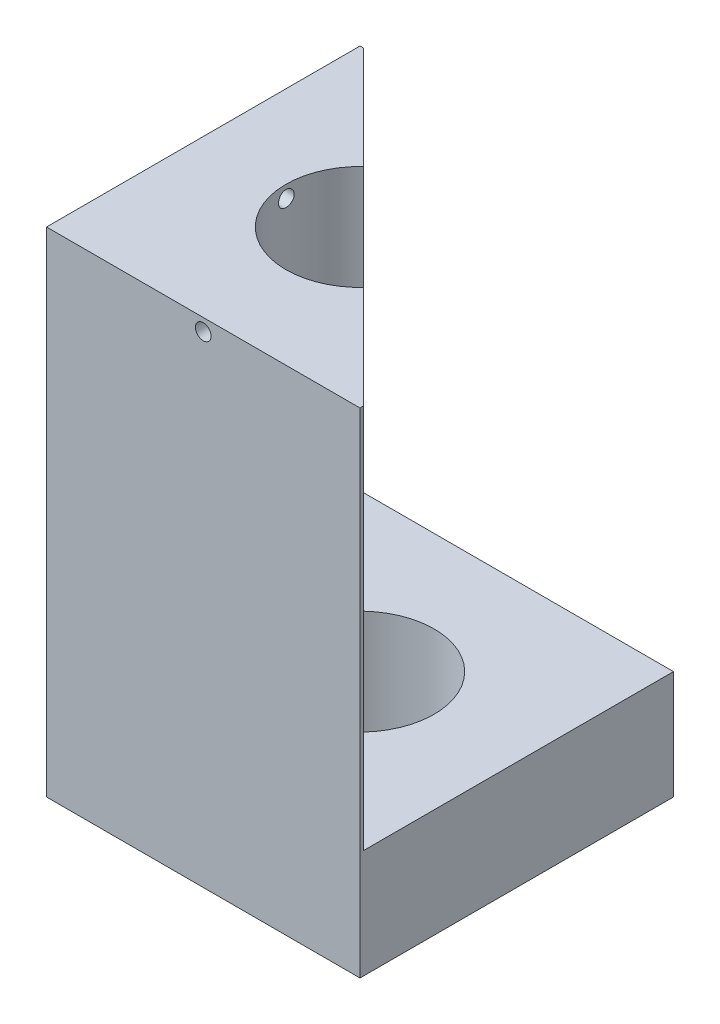
SolidWorks part; units mm, degrees
material "7075-O (SS)"
ref_plane "Front Plane" through (0, 0, 0) normal (0, 0, 1) x (1, 0, 0)
ref_plane "Top Plane" through (0, 0, 0) normal (0, 1, 0) x (1, 0, 0)
ref_plane "Right Plane" through (0, 0, 0) normal (1, 0, 0) x (0, 0, -1)
sketch "Sketch1" plane through (0, 0, 0) normal (0, 1, 0) x (1, 0, 0)
  line L1 (0, 0) -> (12.7, 0)
  line L2 (0, 0) -> (0, 12.7)
  line L3 (0, 12.7) -> (12.7, 12.7)
  line L4 (12.7, 0) -> (12.7, 12.7)
  dimension "D1" = 12.7
  dimension "D2" = 12.7
extrude "Boss-Extrude1" add sketch "Sketch1" along normal blind 20
sketch "Sketch2" plane through (0, 20, 0) normal (0, 1, 0) x (1, 0, 0)
  line L0 (0, 0) -> (12.7, 12.7) construction
  circle A0 centre (6.35, 6.35) radius 3
  dimension "D1" = 6
extrude "Cut-Extrude1" cut sketch "Sketch2" against normal through all
sketch "Sketch3" plane through (0, 20, 0) normal (0, 1, 0) x (1, 0, 0)
  line L0 (0, 12.7) -> (12.7, 0) construction
  line L1 (12.7, 0.1437) -> (0.1437, 12.7)
  line L2 (12.7, 0) -> (12.7, 12.7) construction
  line L3 (12.7, 12.7) -> (0, 12.7) construction
  line L4 (0.1437, 12.7) -> (12.7, 12.7)
  line L5 (12.7, 12.7) -> (12.7, 0.1437)
  dimension "D1" = 0.2032
extrude "Cut-Extrude2" cut sketch "Sketch3" against normal blind 15.6
hole_wizard "#72 (0.025) Diameter Hole1" positions "3DSketch1" profile "Sketch4" hole size "#72" standard "ANSI Inch" end condition up to next
sketch3d "3DSketch1"
  line L0 (0, 20, -6.35) -> (0, 19.5, -6.35) construction
  line L1 (0, 20, -12.7) -> (0, 20, 0) construction
  line L4 (6.35, 20, 0) -> (6.35, 19.5, 0) construction
  line L5 (0, 20, 0) -> (12.7, 20, 0) construction
  point P11 (6.35, 19.5, 0)
  point P13 (0, 19.5, -6.35)
  dimension "D1" = 0.5
sketch "Sketch4" plane through (6.35, 19.5, 0) normal (1, 0, 0) x (0, -1, 0)
  line L0 (0, 0) -> (0, 3.35)
  line L1 (0, 3.35) -> (0.3175, 3.35)
  line L2 (0.3175, 3.35) -> (0.3175, 0)
  line L5 (0.3175, 0) -> (0, 0)
  line L11 (0, -6.35) -> (0, 107.95) construction
  dimension "Thru Hole Dia." = 0.635
  dimension "Thru Hole Depth" = 3.35
